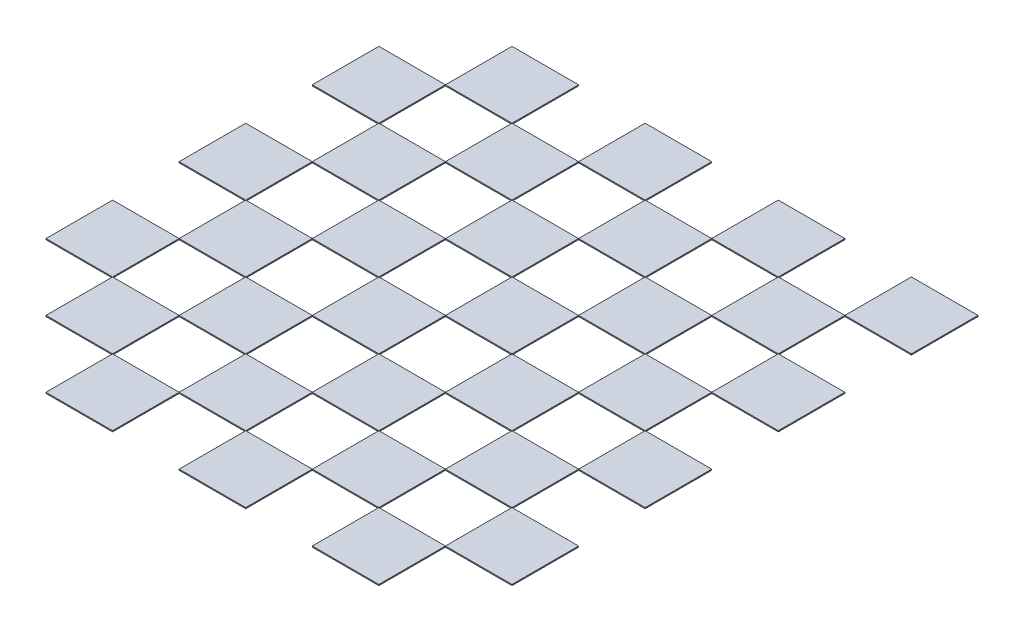
SolidWorks part; units mm, degrees
ref_plane "Front Plane" through (0, 0, 0) normal (0, 0, 1) x (1, 0, 0)
ref_plane "Top Plane" through (0, 0, 0) normal (0, 1, 0) x (1, 0, 0)
ref_plane "Right Plane" through (0, 0, 0) normal (1, 0, 0) x (0, 0, -1)
sketch "Sketch1" plane through (0, 0, 0) normal (0, 1, 0) x (1, 0, 0)
  line L1 (-100, -100) -> (100, -100) construction
  line L2 (-100, -100) -> (-100, 100) construction
  line L3 (-100, 100) -> (100, 100) construction
  line L4 (100, -100) -> (100, 100) construction
  line L5 (-100, -100) -> (100, 100) construction
  line L6 (-100, 100) -> (100, -100) construction
  line L7 (-100, 100) -> (-75, 100)
  line L8 (-100, 100) -> (-100, 75)
  line L9 (-100, 75) -> (-75, 75)
  line L10 (-75, 100) -> (-75, 75)
  line L38 (-75, 100) -> (-75, 75)
  line L39 (-75, 100) -> (-50, 100)
  line L40 (-50, 100) -> (-50, 75)
  line L41 (-75, 75) -> (-50, 75)
  line L42 (-50, 100) -> (-50, 75)
  line L43 (-50, 100) -> (-25, 100)
  line L44 (-25, 100) -> (-25, 75)
  line L45 (-50, 75) -> (-25, 75)
  line L46 (-25, 100) -> (-25, 75)
  line L47 (-25, 100) -> (0, 100)
  line L48 (0, 100) -> (0, 75)
  line L49 (-25, 75) -> (0, 75)
  line L50 (0, 100) -> (0, 75)
  line L51 (0, 100) -> (25, 100)
  line L52 (25, 100) -> (25, 75)
  line L53 (0, 75) -> (25, 75)
  line L54 (25, 100) -> (25, 75)
  line L55 (25, 100) -> (50, 100)
  line L56 (50, 100) -> (50, 75)
  line L57 (25, 75) -> (50, 75)
  line L58 (50, 100) -> (50, 75)
  line L59 (50, 100) -> (75, 100)
  line L60 (75, 100) -> (75, 75)
  line L61 (50, 75) -> (75, 75)
  line L62 (75, 100) -> (75, 75)
  line L63 (75, 100) -> (100, 100)
  line L64 (100, 100) -> (100, 75)
  line L65 (75, 75) -> (100, 75)
  line L66 (-75, 75) -> (-75, 50)
  line L67 (-75, 75) -> (-50, 75)
  line L68 (-50, 75) -> (-50, 50)
  line L69 (-75, 50) -> (-50, 50)
  line L70 (-50, 75) -> (-50, 50)
  line L71 (-50, 75) -> (-25, 75)
  line L72 (-25, 75) -> (-25, 50)
  line L73 (-50, 50) -> (-25, 50)
  line L74 (-25, 75) -> (-25, 50)
  line L75 (-25, 75) -> (0, 75)
  line L76 (0, 75) -> (0, 50)
  line L77 (-25, 50) -> (0, 50)
  line L78 (0, 75) -> (0, 50)
  line L79 (0, 75) -> (25, 75)
  line L80 (25, 75) -> (25, 50)
  line L81 (0, 50) -> (25, 50)
  line L82 (25, 75) -> (25, 50)
  line L83 (25, 75) -> (50, 75)
  line L84 (50, 75) -> (50, 50)
  line L85 (25, 50) -> (50, 50)
  line L86 (50, 75) -> (50, 50)
  line L87 (50, 75) -> (75, 75)
  line L88 (75, 75) -> (75, 50)
  line L89 (50, 50) -> (75, 50)
  line L90 (75, 75) -> (75, 50)
  line L91 (75, 75) -> (100, 75)
  line L92 (100, 75) -> (100, 50)
  line L93 (75, 50) -> (100, 50)
  line L94 (-75, 50) -> (-75, 25)
  line L95 (-75, 50) -> (-50, 50)
  line L96 (-50, 50) -> (-50, 25)
  line L97 (-75, 25) -> (-50, 25)
  line L98 (-50, 50) -> (-50, 25)
  line L99 (-50, 50) -> (-25, 50)
  line L100 (-25, 50) -> (-25, 25)
  line L101 (-50, 25) -> (-25, 25)
  line L102 (-25, 50) -> (-25, 25)
  line L103 (-25, 50) -> (0, 50)
  line L104 (0, 50) -> (0, 25)
  line L105 (-25, 25) -> (0, 25)
  line L106 (0, 50) -> (0, 25)
  line L107 (0, 50) -> (25, 50)
  line L108 (25, 50) -> (25, 25)
  line L109 (0, 25) -> (25, 25)
  line L110 (25, 50) -> (25, 25)
  line L111 (25, 50) -> (50, 50)
  line L112 (50, 50) -> (50, 25)
  line L113 (25, 25) -> (50, 25)
  line L114 (50, 50) -> (50, 25)
  line L115 (50, 50) -> (75, 50)
  line L116 (75, 50) -> (75, 25)
  line L117 (50, 25) -> (75, 25)
  line L118 (75, 50) -> (75, 25)
  line L119 (75, 50) -> (100, 50)
  line L120 (100, 50) -> (100, 25)
  line L121 (75, 25) -> (100, 25)
  line L122 (-75, 25) -> (-75, 0)
  line L123 (-75, 25) -> (-50, 25)
  line L124 (-50, 25) -> (-50, 0)
  line L125 (-75, 0) -> (-50, 0)
  line L126 (-50, 25) -> (-50, 0)
  line L127 (-50, 25) -> (-25, 25)
  line L128 (-25, 25) -> (-25, 0)
  line L129 (-50, 0) -> (-25, 0)
  line L130 (-25, 25) -> (-25, 0)
  line L131 (-25, 25) -> (0, 25)
  line L132 (0, 25) -> (0, 0)
  line L133 (-25, 0) -> (0, 0)
  line L134 (0, 25) -> (0, 0)
  line L135 (0, 25) -> (25, 25)
  line L136 (25, 25) -> (25, 0)
  line L137 (0, 0) -> (25, 0)
  line L138 (25, 25) -> (25, 0)
  line L139 (25, 25) -> (50, 25)
  line L140 (50, 25) -> (50, 0)
  line L141 (25, 0) -> (50, 0)
  line L142 (50, 25) -> (50, 0)
  line L143 (50, 25) -> (75, 25)
  line L144 (75, 25) -> (75, 0)
  line L145 (50, 0) -> (75, 0)
  line L146 (75, 25) -> (75, 0)
  line L147 (75, 25) -> (100, 25)
  line L148 (100, 25) -> (100, 0)
  line L149 (75, 0) -> (100, 0)
  line L150 (-75, 0) -> (-75, -25)
  line L151 (-75, 0) -> (-50, 0)
  line L152 (-50, 0) -> (-50, -25)
  line L153 (-75, -25) -> (-50, -25)
  line L154 (-50, 0) -> (-50, -25)
  line L155 (-50, 0) -> (-25, 0)
  line L156 (-25, 0) -> (-25, -25)
  line L157 (-50, -25) -> (-25, -25)
  line L158 (-25, 0) -> (-25, -25)
  line L159 (-25, 0) -> (0, 0)
  line L160 (0, 0) -> (0, -25)
  line L161 (-25, -25) -> (0, -25)
  line L162 (0, 0) -> (0, -25)
  line L163 (0, 0) -> (25, 0)
  line L164 (25, 0) -> (25, -25)
  line L165 (0, -25) -> (25, -25)
  line L166 (25, 0) -> (25, -25)
  line L167 (25, 0) -> (50, 0)
  line L168 (50, 0) -> (50, -25)
  line L169 (25, -25) -> (50, -25)
  line L170 (50, 0) -> (50, -25)
  line L171 (50, 0) -> (75, 0)
  line L172 (75, 0) -> (75, -25)
  line L173 (50, -25) -> (75, -25)
  line L174 (75, 0) -> (75, -25)
  line L175 (75, 0) -> (100, 0)
  line L176 (100, 0) -> (100, -25)
  line L177 (75, -25) -> (100, -25)
  line L178 (-75, -25) -> (-75, -50)
  line L179 (-75, -25) -> (-50, -25)
  line L180 (-50, -25) -> (-50, -50)
  line L181 (-75, -50) -> (-50, -50)
  line L182 (-50, -25) -> (-50, -50)
  line L183 (-50, -25) -> (-25, -25)
  line L184 (-25, -25) -> (-25, -50)
  line L185 (-50, -50) -> (-25, -50)
  line L186 (-25, -25) -> (-25, -50)
  line L187 (-25, -25) -> (0, -25)
  line L188 (0, -25) -> (0, -50)
  line L189 (-25, -50) -> (0, -50)
  line L190 (0, -25) -> (0, -50)
  line L191 (0, -25) -> (25, -25)
  line L192 (25, -25) -> (25, -50)
  line L193 (0, -50) -> (25, -50)
  line L194 (25, -25) -> (25, -50)
  line L195 (25, -25) -> (50, -25)
  line L196 (50, -25) -> (50, -50)
  line L197 (25, -50) -> (50, -50)
  line L198 (50, -25) -> (50, -50)
  line L199 (50, -25) -> (75, -25)
  line L200 (75, -25) -> (75, -50)
  line L201 (50, -50) -> (75, -50)
  line L202 (75, -25) -> (75, -50)
  line L203 (75, -25) -> (100, -25)
  line L204 (100, -25) -> (100, -50)
  line L205 (75, -50) -> (100, -50)
  line L206 (-75, -50) -> (-75, -75)
  line L207 (-75, -50) -> (-50, -50)
  line L208 (-50, -50) -> (-50, -75)
  line L209 (-75, -75) -> (-50, -75)
  line L210 (-50, -50) -> (-50, -75)
  line L211 (-50, -50) -> (-25, -50)
  line L212 (-25, -50) -> (-25, -75)
  line L213 (-50, -75) -> (-25, -75)
  line L214 (-25, -50) -> (-25, -75)
  line L215 (-25, -50) -> (0, -50)
  line L216 (0, -50) -> (0, -75)
  line L217 (-25, -75) -> (0, -75)
  line L218 (0, -50) -> (0, -75)
  line L219 (0, -50) -> (25, -50)
  line L220 (25, -50) -> (25, -75)
  line L221 (0, -75) -> (25, -75)
  line L222 (25, -50) -> (25, -75)
  line L223 (25, -50) -> (50, -50)
  line L224 (50, -50) -> (50, -75)
  line L225 (25, -75) -> (50, -75)
  line L226 (50, -50) -> (50, -75)
  line L227 (50, -50) -> (75, -50)
  line L228 (75, -50) -> (75, -75)
  line L229 (50, -75) -> (75, -75)
  line L230 (75, -50) -> (75, -75)
  line L231 (75, -50) -> (100, -50)
  line L232 (100, -50) -> (100, -75)
  line L233 (75, -75) -> (100, -75)
  line L234 (-75, -75) -> (-75, -100)
  line L235 (-75, -75) -> (-50, -75)
  line L236 (-50, -75) -> (-50, -100)
  line L237 (-75, -100) -> (-50, -100)
  line L238 (-50, -75) -> (-50, -100)
  line L239 (-50, -75) -> (-25, -75)
  line L240 (-25, -75) -> (-25, -100)
  line L241 (-50, -100) -> (-25, -100)
  line L242 (-25, -75) -> (-25, -100)
  line L243 (-25, -75) -> (0, -75)
  line L244 (0, -75) -> (0, -100)
  line L245 (-25, -100) -> (0, -100)
  line L246 (0, -75) -> (0, -100)
  line L247 (0, -75) -> (25, -75)
  line L248 (25, -75) -> (25, -100)
  line L249 (0, -100) -> (25, -100)
  line L250 (25, -75) -> (25, -100)
  line L251 (25, -75) -> (50, -75)
  line L252 (50, -75) -> (50, -100)
  line L253 (25, -100) -> (50, -100)
  line L254 (50, -75) -> (50, -100)
  line L255 (50, -75) -> (75, -75)
  line L256 (75, -75) -> (75, -100)
  line L257 (50, -100) -> (75, -100)
  line L258 (75, -75) -> (75, -100)
  line L259 (75, -75) -> (100, -75)
  line L260 (100, -75) -> (100, -100)
  line L261 (75, -100) -> (100, -100)
  line L262 (-100, 75) -> (-100, 50)
  line L263 (-100, 75) -> (-75, 75)
  line L264 (-75, 75) -> (-75, 50)
  line L265 (-100, 50) -> (-75, 50)
  line L266 (-100, 50) -> (-100, 25)
  line L267 (-100, 50) -> (-75, 50)
  line L268 (-75, 50) -> (-75, 25)
  line L269 (-100, 25) -> (-75, 25)
  line L270 (-100, 25) -> (-100, 0)
  line L271 (-100, 25) -> (-75, 25)
  line L272 (-75, 25) -> (-75, 0)
  line L273 (-100, 0) -> (-75, 0)
  line L274 (-100, 0) -> (-100, -25)
  line L275 (-100, 0) -> (-75, 0)
  line L276 (-75, 0) -> (-75, -25)
  line L277 (-100, -25) -> (-75, -25)
  line L278 (-100, -25) -> (-100, -50)
  line L279 (-100, -25) -> (-75, -25)
  line L280 (-75, -25) -> (-75, -50)
  line L281 (-100, -50) -> (-75, -50)
  line L282 (-100, -50) -> (-100, -75)
  line L283 (-100, -50) -> (-75, -50)
  line L284 (-75, -50) -> (-75, -75)
  line L285 (-100, -75) -> (-75, -75)
  line L286 (-100, -75) -> (-100, -100)
  line L287 (-100, -75) -> (-75, -75)
  line L288 (-75, -75) -> (-75, -100)
  line L289 (-100, -100) -> (-75, -100)
  line L290 (-100, 100) -> (-75, 100) construction
  line L291 (-100, 100) -> (-100, 75) construction
  point P0 (0, 0)
  dimension "D1" = 200
  dimension "D2" = 25
  dimension "D5" = 25
  dimension "D6" = 25
  dimension "D7" = 90
  dimension "D3" = 8
  dimension "D4" = 8
extrude "Boss-Extrude1" add sketch "Sketch1" along normal blind 0.4 contours L206 L209 L208 L181 | L236 L241 L240 L213 | L212 L217 L216 L189 | L244 L249 L248 L221 | L220 L225 L224 L197 | L252 L257 L256 L229 | L228 L233 L232 L205 | L196 L201 L200 L173 | L164 L169 L168 L141 | L188 L193 L192 L165 | L180 L185 L184 L157 | L278 L281 L178 L277 | L150 L153 L152 L125 | L270 L273 L122 L269 | L94 L97 L96 L69 | L262 L265 L66 L9 | L10 L41 L40 L39 | L68 L73 L72 L45 | L44 L49 L48 L47 | L76 L81 L80 L53 | L52 L57 L56 L55 | L84 L89 L88 L61 | L116 L121 L120 L93 | L140 L145 L144 L117 | L172 L177 L176 L149 | L108 L113 L112 L85 | L132 L137 L136 L109 | L100 L105 L104 L77 | L124 L129 L128 L101 | L156 L161 L160 L133 | L62 L65 L64 L63
